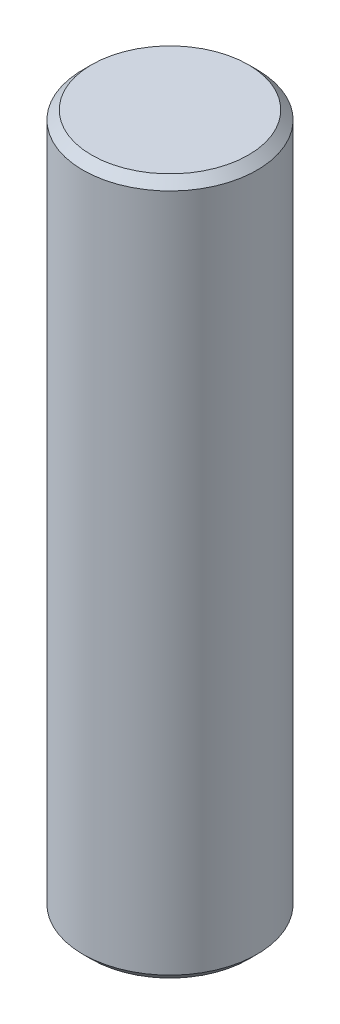
SolidWorks part; units mm, degrees
ref_plane "Front Plane" through (0, 0, 0) normal (0, 0, 1) x (1, 0, 0)
ref_plane "Top Plane" through (0, 0, 0) normal (0, 1, 0) x (1, 0, 0)
ref_plane "Right Plane" through (0, 0, 0) normal (1, 0, 0) x (0, 0, -1)
sketch "Sketch1" plane through (0, 0, 0) normal (0, 1, 0) x (1, 0, 0)
  circle A0 centre (0, 0) radius 1
  dimension "D1" = 2
extrude "Boss-Extrude1" add sketch "Sketch1" along normal mid plane 8
chamfer "Chamfer1" distance 0.1 angle 45 2 edges at (0, -4, 1) (0, 4, 1)
